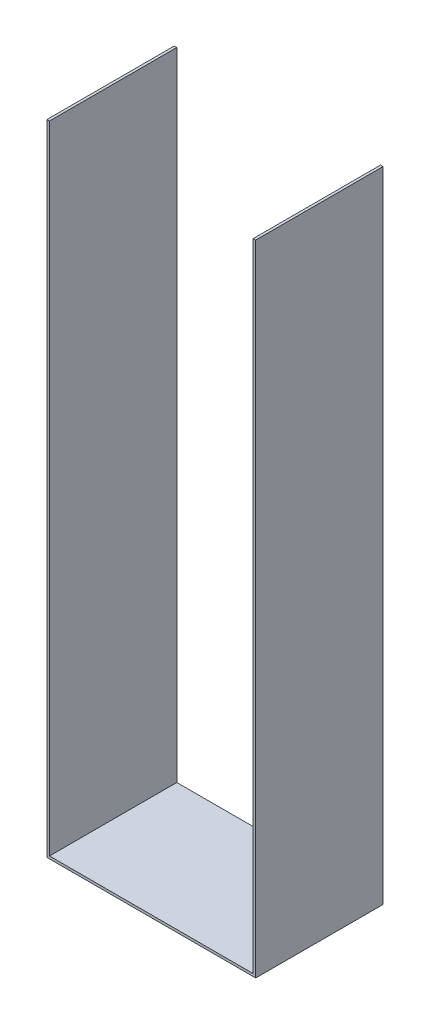
SolidWorks part; units mm, degrees
ref_plane "Front Plane" through (0, 0, 0) normal (0, 0, 1) x (1, 0, 0)
ref_plane "Top Plane" through (0, 0, 0) normal (0, 1, 0) x (1, 0, 0)
ref_plane "Right Plane" through (0, 0, 0) normal (1, 0, 0) x (0, 0, -1)
sketch "Sketch2" plane through (0, 0, 0) normal (0, 0, 1) x (1, 0, 0)
  line L0 (0, 0) -> (0, -50000)
  line L1 (0, -50000) -> (16000, -50000)
  line L2 (16000, -50000) -> (16000, 0)
  line L3 (-200, 0) -> (-200, -50200)
  line L4 (-200, -50200) -> (16200, -50200)
  line L5 (16200, -50200) -> (16200, 0)
  line L6 (-200, 0) -> (0, 0)
  line L7 (16000, 0) -> (16200, 0)
extrude "Boss-Extrude1" add sketch "Sketch2" against normal blind 10000
